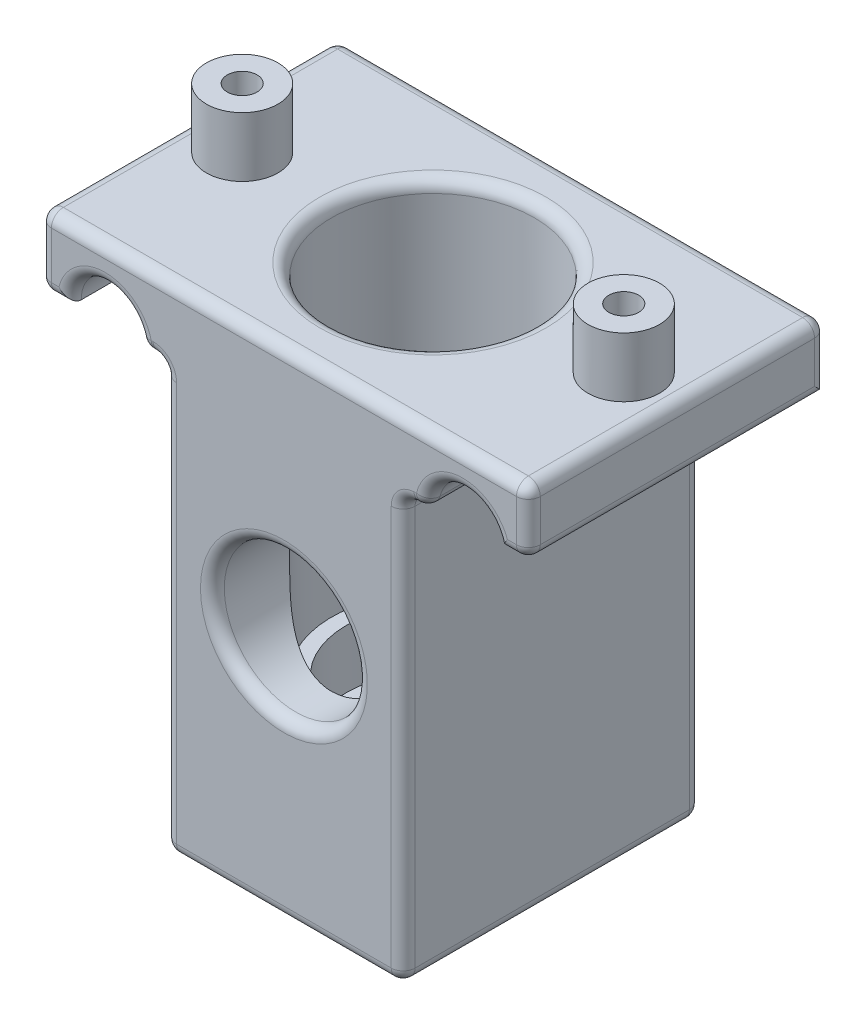
SolidWorks part; units mm, degrees
ref_plane "Alzado" through (0, 0, 0) normal (0, 0, 1) x (1, 0, 0)
ref_plane "Planta" through (0, 0, 0) normal (0, 1, 0) x (1, 0, 0)
ref_plane "Vista lateral" through (0, 0, 0) normal (1, 0, 0) x (0, 0, -1)
sketch "Croquis1" plane through (0, 0, 0) normal (0, 0, 1) x (1, 0, 0)
  line L0 (0, -23.0972) -> (0, 24.4057) construction
  line L1 (-20.5, 20.9065) -> (20.5, 20.9065) construction
  line L2 (-10, 14.909) -> (0, 14.909) construction
  line L3 (0, 14.909) -> (10, 14.909) construction
  line L13 (-18.0018, 14.9394) -> (-20.5, 14.9394)
  line L14 (-20.5, 20.9065) -> (-20.5, 14.9394)
  line L15 (-20.5, 20.9065) -> (20.5, 20.9065)
  line L16 (20.5, 20.9065) -> (20.5, 15.4065)
  line L17 (20.5, 15.4065) -> (17.9723, 15.4065)
  line L19 (-12.0018, 14.9394) -> (-10, 14.909)
  line L20 (-10, 14.909) -> (-10, -20.591)
  line L22 (12, 15) -> (10, 14.909)
  line L23 (10, 14.909) -> (10, -20.591)
  line L24 (10, -20.591) -> (-10, -20.591)
  arc A0 (-18.0018, 14.9394) -> (-12.0018, 14.9394) centre (-15.0018, 14.9394) cw
  arc A1 (12, 15) -> (17.9723, 15.4065) centre (15, 15) cw
  circle A2 centre (0, 0) radius 6
  point P0 (0, 0)
  dimension "D2" = 3
  dimension "D7" = 12
  dimension "D1" = 41
  dimension "D3" = 10
  dimension "D4" = 5.5
  dimension "D5" = 15
  dimension "D6" = 35.5
extrude "Saliente-Extruir1" add sketch "Croquis1" along normal mid plane 25
sketch "Croquis2" plane through (0, 20.9065, 0) normal (0, 1, 0) x (1, 0, 0)
  circle A0 centre (0, 0) radius 8.5
  dimension "D1" = 17
extrude "Cortar-Extruir1" cut sketch "Croquis2" against normal blind 30
fillet "Redondeo2" radius 1 33 edges at (-11.0009, 14.9242, -12.5) (11, 14.9545, -12.5) (0, -20.591, -12.5) (-20.5, 14.9394, 0) (-20.5, 17.9229, -12.5) (-10, 14.909, 0) (-10, -20.591, 0) (-10, -2.841, -12.5) (20.5, 15.4065, 0) (20.5, 18.1565, -12.5) (6, 0, 12.5) (20.5, 18.1565, 12.5) (19.2362, 15.4065, 12.5) (14.7963, 17.9931, 12.5) (11, 14.9545, 12.5) (0, -20.591, 12.5) (-10, -2.841, 12.5) (-11.0009, 14.9242, 12.5) (-15.0018, 17.9394, 12.5) (-19.2509, 14.9394, 12.5) (-20.5, 17.9229, 12.5) (10, -20.591, 0) (10, -2.841, 12.5) (10, 14.909, 0) (10, -2.841, -12.5) (20.5, 20.9065, 0) (0, 20.9065, 12.5) (-20.5, 20.9065, 0) (0, 20.9065, -12.5) (0, 20.9065, 8.5) (6, 0, -12.5) (-12.0018, 14.9394, 0) (12, 15, 0)
sketch "Croquis5" plane through (0, 20.9065, 0) normal (0, 1, 0) x (1, 0, 0)
  line L0 (-16, 0) -> (0, 0) construction
  line L1 (0, 0) -> (16, 0) construction
  circle A0 centre (-16, 0) radius 3
  circle A1 centre (16, 0) radius 3
  dimension "D1" = 16
  dimension "D2" = 6
extrude "Saliente-Extruir2" add sketch "Croquis5" along normal blind 5
hole_wizard "Perforador para roscar para macho de roscar para M3x0.51" positions "Croquis7" profile "Croquis8" hole size "M3x0.5" standard "Ansi Metric"
sketch "Croquis7" plane through (0, 25.9065, 0) normal (0, 1, 0) x (1, 0, 0)
  point P0 (-16, 0)
  point P4 (16, 0)
sketch "Croquis8" plane through (-16, 25.9065, 0) normal (1, 0, 0) x (0, 0, 1)
  line L0 (0, 0) -> (0, 5.7511)
  line L1 (0, 5.7511) -> (1.25, 5)
  line L2 (1.25, 5) -> (1.25, 0)
  line L5 (1.25, 0) -> (0, 0)
  line L10 (0, 5.7511) -> (-1.25, 5) construction
  line L11 (0, -6.35) -> (0, 107.95) construction
  dimension "Diámetro de taladro" = 2.5
  dimension "Profundidad de taladro" = 5
  dimension "Ángulo de perforador" = 118
hole_wizard "Refrentado para perno con cabeza hexagonal de M61" positions "Croquis12" profile "Croquis13" counterbore size "M6" standard "Ansi Metric" end condition through all
sketch "Croquis12" plane through (0, -9.0935, 0) normal (0, 1, 0) x (1, 0, 0)
  point P0 (0, 0)
sketch "Croquis13" plane through (0, -9.0935, 0) normal (1, 0, 0) x (0, 0, 1)
  line L0 (0, 0) -> (0, 11.4975)
  line L1 (0, 11.4975) -> (3.3, 11.4975)
  line L3 (3.3, 11.4975) -> (3.3, 4.88)
  line L4 (3.3, 4.88) -> (7.275, 4.88)
  line L5 (7.275, 4.88) -> (7.275, 0)
  line L7 (7.275, 0) -> (0, 0)
  line L11 (0, -6.35) -> (0, 107.95) construction
  dimension "Diámetro de taladro hasta el siguiente" = 6.6
  dimension "Profundidad de taladro hasta el siguiente" = 11.4975
  dimension "Diámetro de refrentado" = 14.55
  dimension "Profundidad de refrentado" = 4.88
